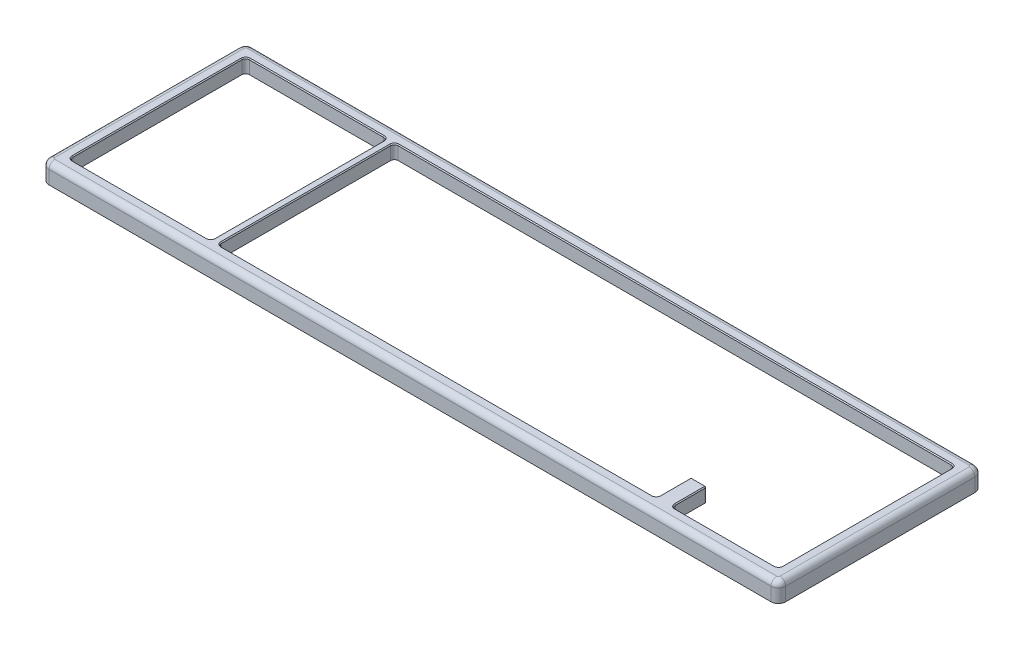
SolidWorks part; units mm, degrees
ref_plane "Front" through (0, 0, 0) normal (0, 0, 1) x (1, 0, 0)
ref_plane "Top" through (0, 0, 0) normal (0, 1, 0) x (1, 0, 0)
ref_plane "Right" through (0, 0, 0) normal (1, 0, 0) x (0, 0, -1)
sketch "Sketch1" plane through (0, 0, 0) normal (0, 1, 0) x (1, 0, 0)
  line L1 (0, 0) -> (401, 0)
  line L2 (0, 0) -> (0, 111)
  line L3 (0, 111) -> (401, 111)
  line L4 (401, 0) -> (401, 111)
  point P7 (0, 0)
  point P12 (401, 111)
  point P15 (401, 0)
  dimension "D1" = 401
  dimension "D2" = 111
extrude "Boss-Extrude1" add sketch "Sketch1" along normal blind 10.5
sketch "Sketch2" plane through (0, 0, 0) normal (0, -1, 0) x (1, 0, 0)
  line L0 (0, 0) -> (401, 0) construction
  line L1 (8, -2) -> (393, -2)
  line L2 (2, -8) -> (2, -103)
  line L3 (8, -109) -> (393, -109)
  line L4 (399, -8) -> (399, -103)
  line L5 (0, -111) -> (0, 0) construction
  line L6 (401, -111) -> (0, -111) construction
  line L7 (401, 0) -> (401, -111) construction
  arc A0 (2, -103) -> (8, -109) centre (8, -103) ccw
  arc A1 (393, -109) -> (399, -103) centre (393, -103) ccw
  arc A2 (393, -2) -> (399, -8) centre (393, -8) cw
  arc A3 (8, -2) -> (2, -8) centre (8, -8) ccw
  dimension "D5" = 6
  dimension "D1" = 2
  dimension "D2" = 2
  dimension "D3" = 2
  dimension "D4" = 2
extrude "Cut-Extrude1" cut sketch "Sketch2" against normal blind 3
sketch "Sketch3" plane through (0, -9.3, 0) normal (0, -1, 0) x (1, 0, 0)
  line L0 (385.5, -48.8) -> (385.5, -62.2) construction
  line L1 (9.5, -7.5) -> (391.5, -7.5)
  line L2 (7.5, -9.5) -> (7.5, -101.5)
  line L3 (9.5, -103.5) -> (391.5, -103.5)
  line L4 (393.5, -9.5) -> (393.5, -101.5)
  line L5 (281.55, -10.5) -> (294.95, -10.5) construction
  line L6 (10.5, -62.2) -> (10.5, -48.8) construction
  line L7 (24.2, -100.5) -> (10.8, -100.5) construction
  arc A0 (391.5, -7.5) -> (393.5, -9.5) centre (391.5, -9.5) cw
  arc A1 (9.5, -7.5) -> (7.5, -9.5) centre (9.5, -9.5) ccw
  arc A2 (7.5, -101.5) -> (9.5, -103.5) centre (9.5, -101.5) ccw
  arc A6 (393.5, -101.5) -> (391.5, -103.5) centre (391.5, -101.5) cw
  dimension "D5" = 2
  dimension "D6" = 2
  dimension "D1" = 8
  dimension "D2" = 3
  dimension "D3" = 3
  dimension "D4" = 3
extrude "Cut-Extrude2" cut sketch "Sketch3" against normal through all
sketch "Sketch20" plane through (0, 10.5, 0) normal (0, 1, 0) x (1, 0, 0)
  line L0 (391.5, 7.5) -> (9.5, 7.5) construction
  line L1 (327, 7.5) -> (335.5, 7.5)
  line L2 (327, 7.5) -> (327, 25.5)
  line L3 (328, 26.5) -> (334.5, 26.5)
  line L4 (335.5, 7.5) -> (335.5, 25.5)
  line L5 (393.5, 101.5) -> (393.5, 9.5) construction
  arc A0 (334.5, 26.5) -> (335.5, 25.5) centre (334.5, 25.5) cw
  arc A1 (327, 25.5) -> (328, 26.5) centre (328, 25.5) cw
  dimension "D4" = 1
  dimension "D1" = 58
  dimension "D2" = 19
  dimension "D3" = 8.5
extrude "Boss-Extrude2" add sketch "Sketch20" against normal up to surface (7.5 mm away) up to face at (200.5, 3, -55.5)
fillet "Fillet4" radius 2 2 edges at (327, 6.75, -7.5) (335.5, 6.75, -7.5)
sketch "Sketch21" plane through (0, 10.5, 0) normal (0, 1, 0) x (1, 0, 0)
  line L0 (9.5, 103.5) -> (391.5, 103.5) construction
  line L1 (84.5, 103.5) -> (88.5, 103.5)
  line L2 (84.5, 103.5) -> (84.5, 7.5)
  line L3 (84.5, 7.5) -> (88.5, 7.5)
  line L4 (88.5, 103.5) -> (88.5, 7.5)
  line L5 (325, 7.5) -> (9.5, 7.5) construction
  line L6 (7.5, 9.5) -> (7.5, 101.5) construction
  dimension "D1" = 4
  dimension "D2" = 77
extrude "Boss-Extrude3" add sketch "Sketch21" against normal up to surface (7.5 mm away) up to face at (265.875, 3, -36.3491)
fillet "Fillet5" radius 2 4 edges at (88.5, 6.75, -7.5) (84.5, 6.75, -7.5) (84.5, 6.75, -103.5) (88.5, 6.75, -103.5)
fillet "Fillet6" radius 4 4 edges at (0, 5.25, -111) (401, 5.25, -111) (401, 5.25, 0) (0, 5.25, 0)
chamfer "Chamfer2" distance 0.5 angle 45 24 edges at (46, 10.5, -7.5) (8.0858, 10.5, -8.0858) (83.9142, 10.5, -8.0858) (7.5, 10.5, -55.5) (84.5, 10.5, -55.5) (8.0858, 10.5, -102.9142) (83.9142, 10.5, -102.9142) (46, 10.5, -103.5) (331.25, 10.5, -26.5) (335.2071, 10.5, -26.2071) (327.2929, 10.5, -26.2071) (335.5, 10.5, -17.5) (327, 10.5, -17.5) (336.0858, 10.5, -8.0858) (326.4142, 10.5, -8.0858) (364.5, 10.5, -7.5) (207.75, 10.5, -7.5) (392.9142, 10.5, -8.0858) (89.0858, 10.5, -8.0858) (393.5, 10.5, -55.5) (88.5, 10.5, -55.5) (392.9142, 10.5, -102.9142) (89.0858, 10.5, -102.9142) (241, 10.5, -103.5)
fillet "Fillet7" radius 3.175 8 edges at (1.1716, 10.5, -109.8284) (200.5, 10.5, -111) (399.8284, 10.5, -109.8284) (401, 10.5, -55.5) (399.8284, 10.5, -1.1716) (200.5, 10.5, 0) (1.1716, 10.5, -1.1716) (0, 10.5, -55.5)
sketch "Sketch22" plane through (0, 3, 0) normal (0, -1, 0) x (1, 0, 0)
  line L0 (393, -2) -> (8, -2) construction
  line L2 (8, -109) -> (393, -109) construction
  line L3 (2, -8) -> (2, -103) construction
  circle A0 centre (265.625, -5.375) radius 1 construction
  circle A1 centre (5.375, -5.375) radius 1 construction
  circle A2 centre (5.375, -105.625) radius 1 construction
  circle A3 centre (135.375, -105.625) radius 1 construction
  circle A4 centre (135.375, -5.375) radius 1 construction
  circle A5 centre (265.625, -105.625) radius 1 construction
  circle A6 centre (395.625, -5.375) radius 1 construction
  circle A7 centre (395.625, -105.625) radius 1 construction
  dimension "D2" = 130
  dimension "D3" = 130.25
  dimension "D6" = 3.375
  dimension "D7" = 2
  dimension "D1" = 3.375
  dimension "D4" = 130
  dimension "D5" = 3.375
hole_wizard "M2x0.4 Tapped Hole2" positions "3DSketch2" profile "Sketch24" tap size "M2x0.4" standard "ANSI Metric"
sketch3d "3DSketch2"
  point P0 (5.375, 3, -5.375)
  point P3 (135.375, 3, -5.375)
  point P6 (265.625, 3, -5.375)
  point P9 (395.625, 3, -5.375)
  point P12 (395.625, 3, -105.625)
  point P15 (265.625, 3, -105.625)
  point P18 (135.375, 3, -105.625)
  point P21 (5.375, 3, -105.625)
sketch "Sketch24" plane through (5.375, 3, -5.375) normal (1, 0, 0) x (0, 0, -1)
  line L0 (0, 0) -> (0, 6.2307)
  line L1 (0, 6.2307) -> (0.8, 5.75)
  line L2 (0.8, 5.75) -> (0.8, 0)
  line L5 (0.8, 0) -> (0, 0)
  line L10 (0, 6.2307) -> (-0.8, 5.75) construction
  line L11 (0, -6.35) -> (0, 107.95) construction
  dimension "Tap Drill Dia." = 1.6
  dimension "Tap Drill Depth" = 5.75
  dimension "Drill Angle" = 118
cosmetic thread "Hole Thread2" parameters "D1"=5.75, "D2"=2
cosmetic thread "Hole Thread3" parameters "D1"=5.75, "D2"=2
cosmetic thread "Hole Thread4" parameters "D1"=5.75, "D2"=2
cosmetic thread "Hole Thread5" parameters "D1"=5.75, "D2"=2
cosmetic thread "Hole Thread6" parameters "D1"=5.75, "D2"=2
cosmetic thread "Hole Thread7" parameters "D1"=5.75, "D2"=2
cosmetic thread "Hole Thread8" parameters "D1"=5.75, "D2"=2
cosmetic thread "Hole Thread9" parameters "D1"=5.75, "D2"=2
sketch "Sketch25" plane through (0, 3, 0) normal (0, -1, 0) x (1, 0, 0)
  circle A0 centre (70.375, -5.375) radius 1
  circle A1 centre (200.5, -5.375) radius 1
  circle A2 centre (330.625, -5.375) radius 1
  circle A3 centre (330.625, -105.625) radius 1
  circle A4 centre (200.5, -105.625) radius 1
  circle A5 centre (70.375, -105.625) radius 1
  circle A6 centre (5.375, -55.5) radius 1
  circle A7 centre (395.625, -55.5) radius 1
  dimension "D1" = 2
  dimension "D2" = 65
  dimension "D3" = 65.125
  dimension "D4" = 65
  dimension "D5" = 50.125
hole_wizard "M2x0.4 Tapped Hole3" positions "3DSketch3" profile "Sketch26" tap size "M2x0.4" standard "ANSI Metric"
sketch3d "3DSketch3"
  point P0 (70.375, 3, -5.375)
  point P3 (200.5, 3, -5.375)
  point P6 (330.625, 3, -5.375)
  point P9 (395.625, 3, -55.5)
  point P12 (330.625, 3, -105.625)
  point P15 (200.5, 3, -105.625)
  point P18 (70.375, 3, -105.625)
  point P21 (5.375, 3, -55.5)
sketch "Sketch26" plane through (70.375, 3, -5.375) normal (1, 0, 0) x (0, 0, -1)
  line L0 (0, 0) -> (0, 6.2307)
  line L1 (0, 6.2307) -> (0.8, 5.75)
  line L2 (0.8, 5.75) -> (0.8, 0)
  line L5 (0.8, 0) -> (0, 0)
  line L10 (0, 6.2307) -> (-0.8, 5.75) construction
  line L11 (0, -6.35) -> (0, 107.95) construction
  dimension "Tap Drill Dia." = 1.6
  dimension "Tap Drill Depth" = 5.75
  dimension "Drill Angle" = 118
cosmetic thread "Hole Thread10" parameters "D1"=5.75, "D2"=2
cosmetic thread "Hole Thread11" parameters "D1"=5.75, "D2"=2
cosmetic thread "Hole Thread12" parameters "D1"=5.75, "D2"=2
cosmetic thread "Hole Thread13" parameters "D1"=5.75, "D2"=2
cosmetic thread "Hole Thread14" parameters "D1"=5.75, "D2"=2
cosmetic thread "Hole Thread15" parameters "D1"=5.75, "D2"=2
cosmetic thread "Hole Thread16" parameters "D1"=5.75, "D2"=2
cosmetic thread "Hole Thread17" parameters "D1"=5.75, "D2"=2
sketch "Sketch27" plane through (0, 0, 0) normal (0, -1, 0) x (1, 0, 0)
  line L37 (393, -1.75) -> (8, -1.75)
  line L38 (1.75, -8) -> (1.75, -103)
  line L39 (8, -109.25) -> (393, -109.25)
  line L40 (399.25, -103) -> (399.25, -8)
  line L41 (393, -1.75) -> (8, -1.75)
  line L42 (1.75, -8) -> (1.75, -103)
  line L43 (8, -109.25) -> (393, -109.25)
  line L44 (399.25, -103) -> (399.25, -8)
  arc A26 (399.25, -8) -> (393, -1.75) centre (393, -8) ccw
  arc A27 (8, -1.75) -> (1.75, -8) centre (8, -8) ccw
  arc A28 (1.75, -103) -> (8, -109.25) centre (8, -103) ccw
  arc A29 (393, -109.25) -> (399.25, -103) centre (393, -103) ccw
  arc A30 (399.25, -8) -> (393, -1.75) centre (393, -8) ccw
  arc A31 (8, -1.75) -> (1.75, -8) centre (8, -8) ccw
  arc A32 (1.75, -103) -> (8, -109.25) centre (8, -103) ccw
  arc A33 (393, -109.25) -> (399.25, -103) centre (393, -103) ccw
  dimension "D1" = 0.25
extrude "Cut-Extrude3" cut sketch "Sketch27" against normal up to surface (3 mm away) up to face at (70.375, 3, -6.175)
